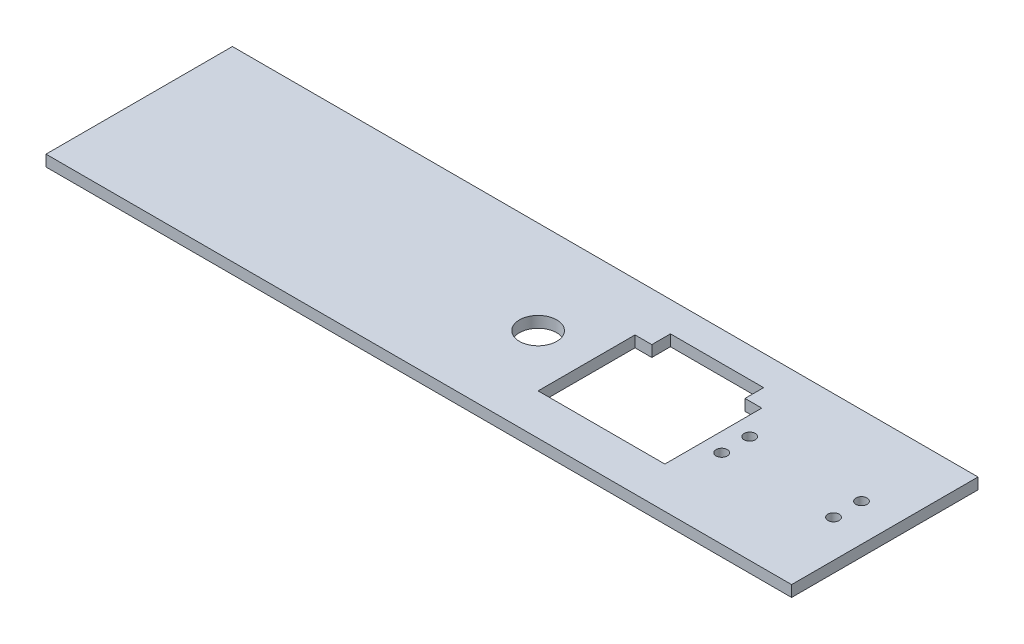
SolidWorks part; units mm, degrees
ref_plane "Front Plane" through (0, 0, 0) normal (0, 0, 1) x (1, 0, 0)
ref_plane "Top Plane" through (0, 0, 0) normal (0, 1, 0) x (1, 0, 0)
ref_plane "Right Plane" through (0, 0, 0) normal (1, 0, 0) x (0, 0, -1)
sketch "Sketch1" plane through (0, 0, 0) normal (0, 1, 0) x (1, 0, 0)
  line L1 (-95, -25) -> (105, -25)
  line L2 (-95, -25) -> (-95, 25)
  line L3 (-95, 25) -> (105, 25)
  line L4 (105, -25) -> (105, 25)
  line L5 (-95, -25) -> (105, 25) construction
  line L6 (-95, 25) -> (105, -25) construction
  point P0 (5, 0)
  dimension "D1" = 200
  dimension "D2" = 50
  dimension "D3" = 5
extrude "Boss-Extrude1" add sketch "Sketch1" along normal mid plane 3
sketch "Sketch3" plane through (0, 1.5, 0) normal (0, 1, 0) x (1, 0, 0)
  line L0 (-95, 0) -> (105, 0) construction
  line L1 (-95, 25) -> (-95, -25) construction
  line L2 (105, -25) -> (105, 25) construction
  circle A0 centre (12, 0) radius 5
  dimension "D2" = 10
  dimension "D1" = 107
extrude "Cut-Extrude2" cut sketch "Sketch3" against normal through all
sketch "Sketch4" plane through (0, 1.5, 0) normal (0, 1, 0) x (1, 0, 0)
  line L0 (105, 0) -> (0, 0) construction
  line L1 (105, -25) -> (105, 25) construction
  line L2 (65, 3.75) -> (105, 3.75) construction
  circle A0 centre (65, 3.75) radius 1.5
  circle A1 centre (95, 3.75) radius 1.5
  circle A2 centre (95, -3.75) radius 1.5
  circle A3 centre (65, -3.75) radius 1.5
  dimension "D1" = 3
  dimension "D2" = 3
  dimension "D3" = 30
  dimension "D4" = 10
  dimension "D5" = 7.5
extrude "Cut-Extrude3" cut sketch "Sketch4" against normal through all both and the other way through all
sketch "Sketch5" plane through (0, 1.5, 0) normal (0, 1, 0) x (1, 0, 0)
  line L0 (12, 0) -> (105, 0) construction
  line L1 (105, -25) -> (105, 25) construction
  line L4 (26, -14) -> (26, 12)
  line L5 (26, 12) -> (60, 12)
  line L6 (60, -14) -> (60, 12)
  line L9 (60, -14) -> (26, -14)
  point P7 (60, -13.6815)
  point P9 (0, 0)
  point P11 (26, -13.7297)
  dimension "D1" = 26
  dimension "D2" = 34
  dimension "D3" = 14
  dimension "D4" = 14
extrude "Cut-Extrude4" cut sketch "Sketch5" against normal through all both and the other way through all
sketch "Sketch6" plane through (0, 1.5, 0) normal (0, 1, 0) x (1, 0, 0)
  line L0 (43, -14) -> (43, 17) construction
  line L1 (60, -14) -> (26, -14) construction
  line L2 (55.5, 17) -> (30.5, 17)
  line L3 (30.5, 17) -> (30.5, 12)
  line L4 (26, 12) -> (60, 12) construction
  line L5 (55.5, 17) -> (55.5, 12)
  line L6 (30.5, 12) -> (55.5, 12)
  dimension "D1" = 25
  dimension "D2" = 5
extrude "Cut-Extrude5" cut sketch "Sketch6" against normal through all both and the other way through all
